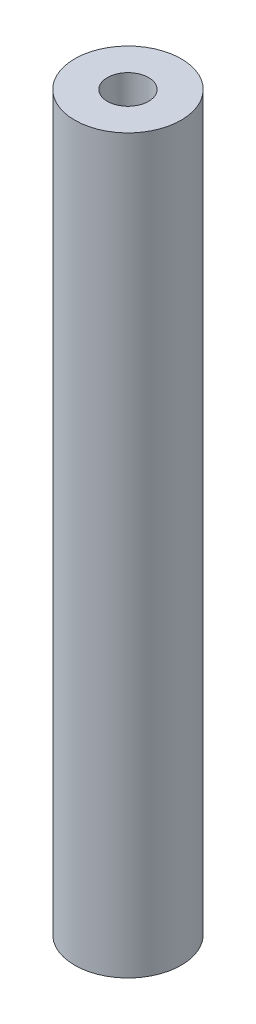
SolidWorks part; units mm, degrees
ref_plane "Ebene vorne" through (0, 0, 0) normal (0, 0, 1) x (1, 0, 0)
ref_plane "Ebene oben" through (0, 0, 0) normal (0, 1, 0) x (1, 0, 0)
ref_plane "Ebene rechts" through (0, 0, 0) normal (1, 0, 0) x (0, 0, -1)
sketch "Skizze1" plane through (0, 0, 0) normal (0, 1, 0) x (1, 0, 0)
  circle A0 centre (0, 0) radius 4
  dimension "D1" = 8
extrude "Aufsatz-Linear austragen1" add sketch "Skizze1" along normal blind 55
sketch "Skizze2" plane through (0, 55, 0) normal (0, 1, 0) x (1, 0, 0)
  circle A0 centre (0, 0) radius 1.55
  dimension "D1" = 3.1
extrude "Schnitt-Linear austragen1" cut sketch "Skizze2" against normal blind 10
sketch "Skizze3" plane through (0, 0, 0) normal (0, -1, 0) x (1, 0, 0)
  circle A0 centre (0, 0) radius 1.65
  dimension "D1" = 3.3
extrude "Schnitt-Linear austragen2" cut sketch "Skizze3" against normal blind 10
